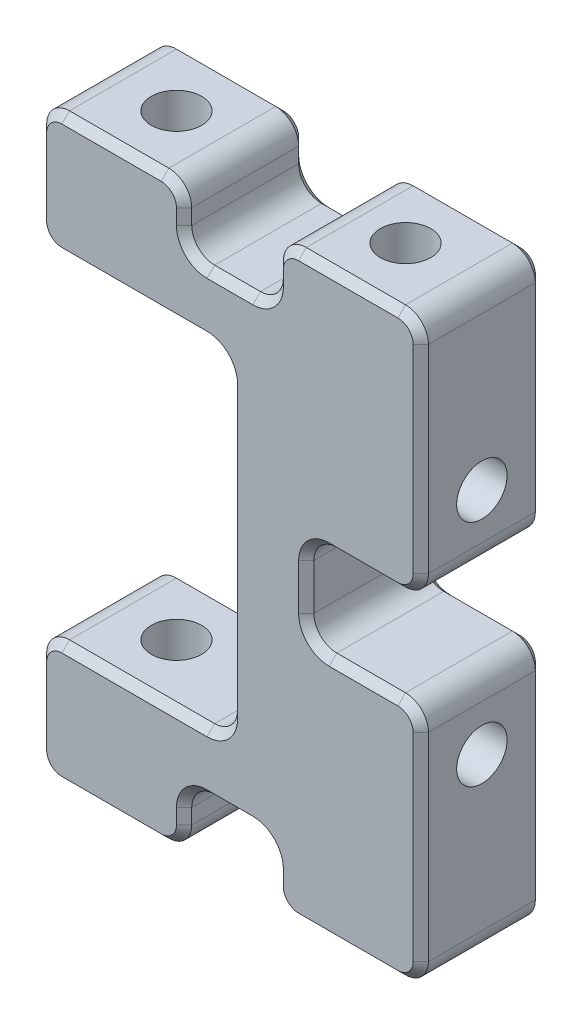
SolidWorks part; units mm, degrees
material "6061 合金"
ref_plane "前视基准面" through (0, 0, 0) normal (0, 0, 1) x (1, 0, 0)
ref_plane "上视基准面" through (0, 0, 0) normal (0, 1, 0) x (1, 0, 0)
ref_plane "右视基准面" through (0, 0, 0) normal (1, 0, 0) x (0, 0, -1)
sketch "草图1" plane through (0, 0, 0) normal (0, 0, 1) x (1, 0, 0)
  line L1 (-12.5, 19) -> (12.5, 19)
  line L2 (-12.5, 19) -> (-12.5, -19)
  line L3 (-12.5, -19) -> (12.5, -19)
  line L4 (12.5, 19) -> (12.5, -19)
  line L5 (-12.5, 19) -> (12.5, -19) construction
  line L6 (-12.5, -19) -> (12.5, 19) construction
  line L7 (-31, 11) -> (0, 11)
  line L8 (-31, 11) -> (-31, -11)
  line L9 (-31, -11) -> (0, -11)
  line L10 (0, 11) -> (0, -11)
  line L11 (-31, 11) -> (0, -11) construction
  line L12 (-31, -11) -> (0, 11) construction
  circle A0 centre (-15.5, 0) radius 11
  point P2 (0, 0)
  dimension "D2" = 22
  dimension "D1" = 28
  dimension "D3" = 25
  dimension "D4" = 38
extrude "凸台-拉伸1" add sketch "草图1" along normal mid plane 8 contours L7 L10 L9 L2 L3 L4 L1
sketch "草图2" plane through (0, 19, 0) normal (0, 1, 0) x (1, 0, 0)
  line L0 (-7.5, 0) -> (7.5, 0) construction
  circle A0 centre (-7.5, 0) radius 1.5
  circle A1 centre (7.5, 0) radius 1.5
  dimension "D2" = 3
  dimension "D1" = 15
extrude "切除-拉伸1" cut sketch "草图2" against normal blind 8
sketch "草图3" plane through (0, 0, 0) normal (-1, 0, 0) x (0, 0, 1)
  line L0 (0, 7.5) -> (0, -7.5) construction
  circle A0 centre (0, 7.5) radius 1.5
  circle A1 centre (0, -7.5) radius 1.5
  dimension "D2" = 3
  dimension "D1" = 15
extrude "切除-拉伸2" cut sketch "草图3" against normal through all
hole_wizard "M4 螺纹孔1" positions "草图5" profile "草图6" tap size "M4" standard "ISO" end condition through all
sketch "草图5" plane through (12.5, 0, 0) normal (1, 0, 0) x (0, 0, -1)
  point P0 (0, 7.5)
  point P3 (0, -7.5)
sketch "草图6" plane through (12.5, 7.5, 0) normal (0, 1, 0) x (0, 0, -1)
  line L0 (0, 0) -> (0, 25)
  line L1 (0, 25) -> (1.65, 25)
  line L2 (1.65, 25) -> (1.65, 0)
  line L5 (1.65, 0) -> (0, 0)
  line L11 (0, -6.35) -> (0, 107.95) construction
  dimension "通孔螺纹孔钻头直径" = 3.3
  dimension "通孔螺纹孔钻头深度" = 25
cosmetic thread "孔螺蚊线1" parameters "D2"=4
cosmetic thread "孔螺蚊线2" parameters "D2"=4
hole_wizard "M4 螺纹孔2" positions "草图7" profile "草图8" tap size "M4" standard "ISO"
sketch "草图7" plane through (0, 19, 0) normal (0, 1, 0) x (1, 0, 0)
  point P0 (-7.5, 0)
  point P3 (7.5, 0)
sketch "草图8" plane through (-7.5, 19, 0) normal (1, 0, 0) x (0, 0, 1)
  line L0 (0, 0) -> (0, 8.9914)
  line L1 (0, 8.9914) -> (1.65, 8)
  line L2 (1.65, 8) -> (1.65, 0)
  line L5 (1.65, 0) -> (0, 0)
  line L10 (0, 8.9914) -> (-1.65, 8) construction
  line L11 (0, -6.35) -> (0, 107.95) construction
  dimension "螺纹孔钻头直径" = 3.3
  dimension "螺纹孔钻头深度" = 8
  dimension "导头角度" = 118
cosmetic thread "孔螺蚊线3" parameters "D1"=8, "D2"=4
cosmetic thread "孔螺蚊线4" parameters "D1"=8, "D2"=4
mirror "镜向1" about plane through (0, 0, 0) normal (0, 1, 0) of "M4 螺纹孔2"
sketch "草图9" plane through (0, 0, 4) normal (0, 0, 1) x (1, 0, 0)
  line L0 (12.5, 19) -> (12.5, -19) construction
  line L1 (20, 3) -> (5, 3)
  line L2 (20, 3) -> (20, -3)
  line L3 (20, -3) -> (5, -3)
  line L4 (5, 3) -> (5, -3)
  line L5 (20, 3) -> (5, -3) construction
  line L6 (20, -3) -> (5, 3) construction
  line L7 (-12.5, 19) -> (12.5, 19) construction
  line L8 (-3, 23) -> (3, 23)
  line L9 (-3, 23) -> (-3, 15)
  line L10 (-3, 15) -> (3, 15)
  line L11 (3, 23) -> (3, 15)
  line L12 (-3, 23) -> (3, 15) construction
  line L13 (-3, 15) -> (3, 23) construction
  line L14 (-12.5, -19) -> (12.5, -19) construction
  line L15 (-3, -15) -> (3, -15)
  line L16 (-3, -15) -> (-3, -23)
  line L17 (-3, -23) -> (3, -23)
  line L18 (3, -15) -> (3, -23)
  line L19 (-3, -15) -> (3, -23) construction
  line L20 (-3, -23) -> (3, -15) construction
  point P0 (12.5, 0)
  point P7 (0, 19)
  point P14 (0, -19)
  dimension "D1" = 6
  dimension "D2" = 15
  dimension "D3" = 6
  dimension "D4" = 8
extrude "切除-拉伸3" cut sketch "草图9" against normal through all
fillet "圆角1" radius 1.5 20 edges at (-12.5, 19, 0) (12.5, 19, 0) (12.5, -19, 0) (-12.5, -19, 0) (-12.5, -11, 0) (0, -11, 0) (0, 11, 0) (-12.5, 11, 0) (5, 3, 0) (5, -3, 0) (12.5, 3, 0) (12.5, -3, 0) (3, -19, 0) (3, -15, 0) (-3, -15, 0) (-3, -19, 0) (-3, 19, 0) (-3, 15, 0) (3, 15, 0) (3, 19, 0)
chamfer "倒角1" distance 0.5 angle 45 80 edges at (7.75, 19, -4) (3.4393, 18.5607, -4) (12.0607, 18.5607, -4) (3, 17, -4) (12.5, 11, -4) (2.5607, 15.4393, -4) (12.0607, 3.4393, -4) (0, 15, -4) (8.75, 3, -4) (-2.5607, 15.4393, -4) (5.4393, 2.5607, -4) (-3, 17, -4) (5, 0, -4) (-3.4393, 18.5607, -4) (5.4393, -2.5607, -4) (-7.75, 19, -4) (8.75, -3, -4) (-12.0607, 18.5607, -4) (12.0607, -3.4393, -4) (-12.5, 15, -4) (12.5, -11, -4) (-12.0607, 11.4393, -4) (12.0607, -18.5607, -4) (-6.25, 11, -4) (7.75, -19, -4) (-0.4393, 10.5607, -4) (3.4393, -18.5607, -4) (0, 0, -4) (3, -17, -4) (-0.4393, -10.5607, -4) (2.5607, -15.4393, -4) (-6.25, -11, -4) (0, -15, -4) (-12.0607, -11.4393, -4) (-2.5607, -15.4393, -4) (-12.5, -15, -4) (-3, -17, -4) (-12.0607, -18.5607, -4) (-3.4393, -18.5607, -4) (-7.75, -19, -4) (8.75, -3, 4) (5.4393, -2.5607, 4) (12.0607, -3.4393, 4) (5, 0, 4) (12.5, -11, 4) (5.4393, 2.5607, 4) (12.0607, -18.5607, 4) (8.75, 3, 4) (7.75, -19, 4) (12.0607, 3.4393, 4) (3.4393, -18.5607, 4) (12.5, 11, 4) (3, -17, 4) (12.0607, 18.5607, 4) (2.5607, -15.4393, 4) (7.75, 19, 4) (0, -15, 4) (3.4393, 18.5607, 4) (-2.5607, -15.4393, 4) (3, 17, 4) (-3, -17, 4) (2.5607, 15.4393, 4) (-3.4393, -18.5607, 4) (0, 15, 4) (-7.75, -19, 4) (-2.5607, 15.4393, 4) (-12.0607, -18.5607, 4) (-3, 17, 4) (-12.5, -15, 4) (-3.4393, 18.5607, 4) (-12.0607, -11.4393, 4) (-7.75, 19, 4) (-6.25, -11, 4) (-12.0607, 18.5607, 4) (-0.4393, -10.5607, 4) (-12.5, 15, 4) (0, 0, 4) (-12.0607, 11.4393, 4) (-0.4393, 10.5607, 4) (-6.25, 11, 4)
